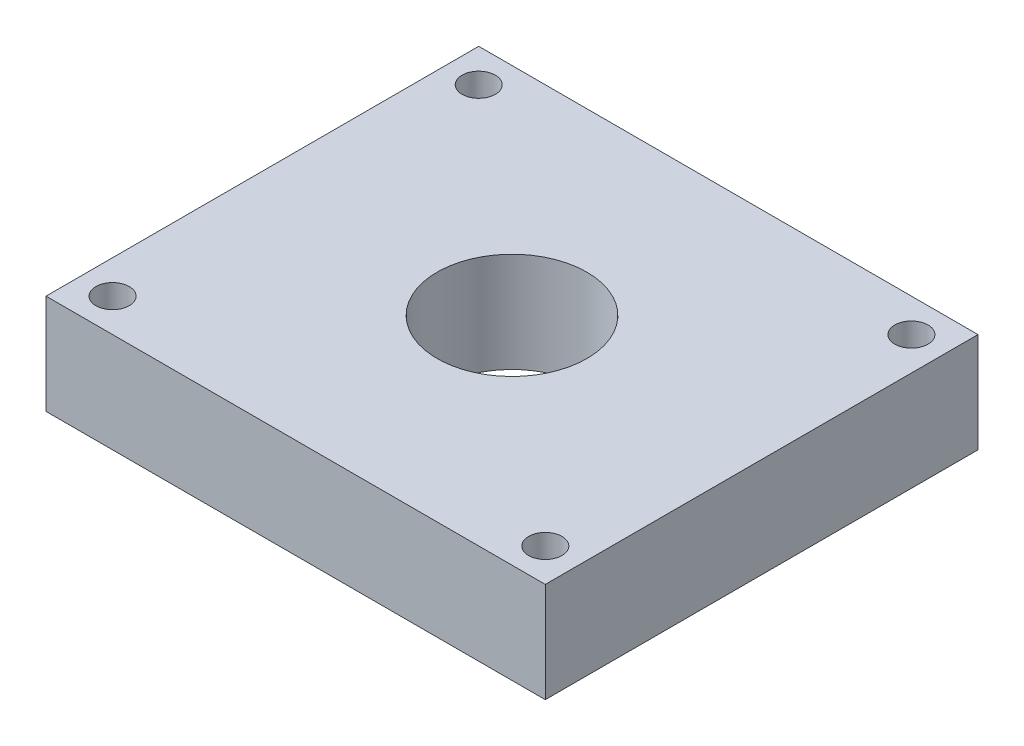
SolidWorks part; units mm, degrees
material "6061-T6 (SS)"
ref_plane "Front Plane" through (0, 0, 0) normal (0, 0, 1) x (1, 0, 0)
ref_plane "Top Plane" through (0, 0, 0) normal (0, 1, 0) x (1, 0, 0)
ref_plane "Right Plane" through (0, 0, 0) normal (1, 0, 0) x (0, 0, -1)
sketch "Sketch1" plane through (0, 0, 0) normal (0, 1, 0) x (1, 0, 0)
  line L0 (-47.625, 0) -> (47.625, 0) construction
  line L1 (-47.625, -41.275) -> (47.625, -41.275)
  line L2 (-47.625, -41.275) -> (-47.625, 41.275)
  line L3 (-47.625, 41.275) -> (47.625, 41.275)
  line L4 (47.625, -41.275) -> (47.625, 41.275)
  line L5 (-47.625, -41.275) -> (47.625, 41.275) construction
  line L6 (-47.625, 41.275) -> (47.625, -41.275) construction
  line L7 (0, 41.275) -> (0, -41.275) construction
  circle A0 centre (0, 0) radius 14.2875
  circle A1 centre (-41.275, 34.925) radius 3.175
  circle A2 centre (-41.275, -34.925) radius 3.175
  circle A3 centre (41.275, 34.925) radius 3.175
  circle A4 centre (41.275, -34.925) radius 3.175
  point P0 (0, 0)
  dimension "D3" = 28.575
  dimension "D4" = 41.275
  dimension "D5" = 6.35
  dimension "D1" = 95.25
  dimension "D2" = 82.55
  dimension "D6" = 34.925
extrude "Boss-Extrude1" add sketch "Sketch1" along normal blind 19.05
